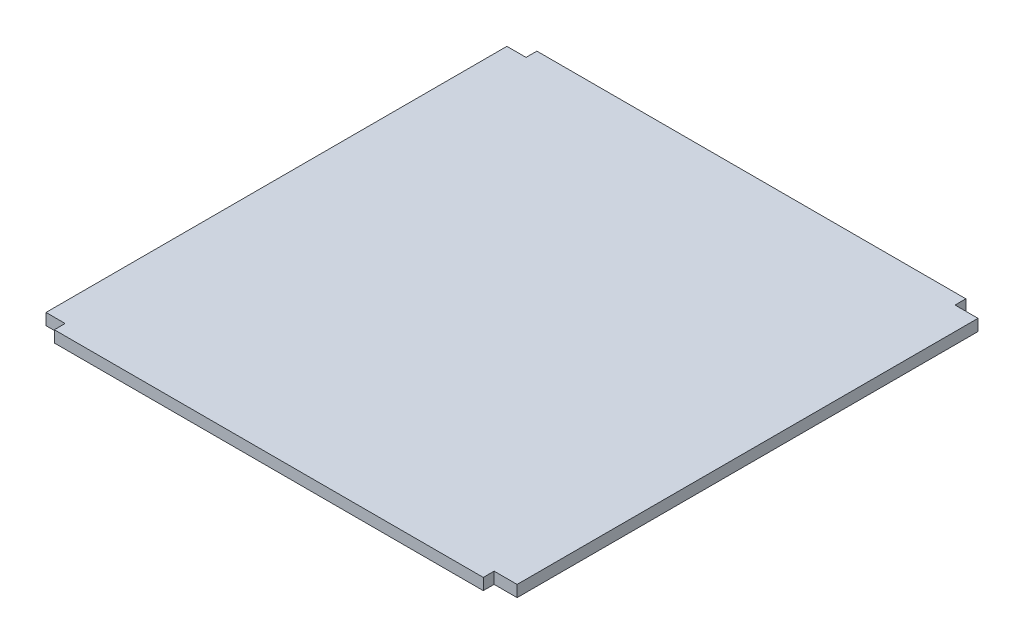
SolidWorks part; units mm, degrees
ref_plane "Front Plane" through (0, 0, 0) normal (0, 0, 1) x (1, 0, 0)
ref_plane "Top Plane" through (0, 0, 0) normal (0, 1, 0) x (1, 0, 0)
ref_plane "Right Plane" through (0, 0, 0) normal (1, 0, 0) x (0, 0, -1)
sketch "Sketch1" plane through (0, 0, 0) normal (0, 1, 0) x (1, 0, 0)
  line L0 (0, 1.415) -> (0, 61.585)
  line L1 (0, 61.585) -> (2.5, 61.585)
  line L2 (2.5, 61.585) -> (2.5, 63)
  line L3 (2.5, 63) -> (58.5, 63)
  line L4 (58.5, 63) -> (58.5, 61.585)
  line L5 (58.5, 61.585) -> (61.5, 61.585)
  line L6 (61.5, 61.585) -> (61.5, 1.415)
  line L7 (61.5, 1.415) -> (58.5, 1.415)
  line L8 (58.5, 1.415) -> (58.5, 0)
  line L9 (58.5, 0) -> (2.5, 0)
  line L10 (2.5, 0) -> (2.5, 1.415)
  line L11 (2.5, 1.415) -> (0, 1.415)
  dimension "D1" = 61.5
  dimension "D2" = 2.5
  dimension "D3" = 63
  dimension "D4" = 60.17
  dimension "D5" = 3
extrude "Boss-Extrude1" add sketch "Sketch1" along normal blind 1.5
